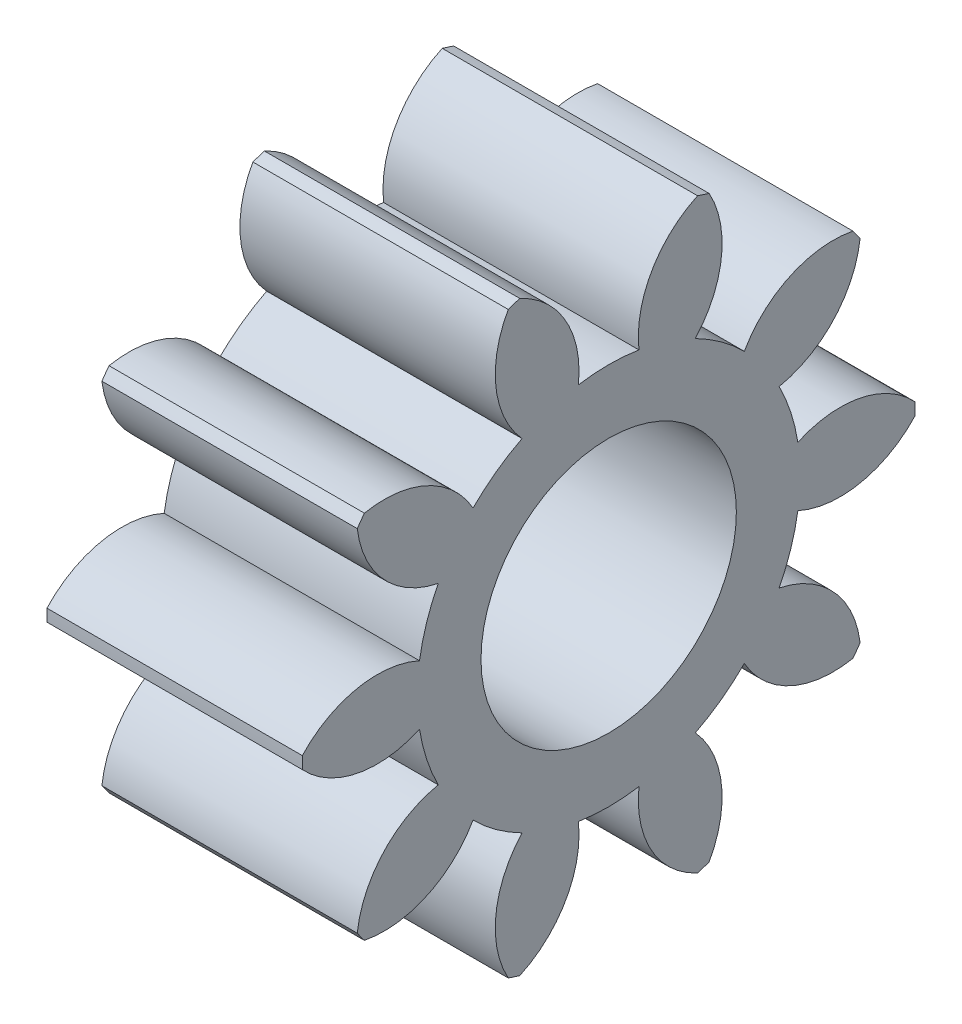
SolidWorks part; units mm, degrees
ref_plane "Plane1" through (0, 0, 0) normal (0, 0, 1) x (1, 0, 0)
ref_plane "Plane2" through (0, 0, 0) normal (0, 1, 0) x (1, 0, 0)
ref_plane "Plane3" through (0, 0, 0) normal (1, 0, 0) x (0, 0, -1)
sketch "HoldingSke" plane through (0, 0, 0) normal (0, 1, 0) x (1, 0, 0)
  line L0 (0, 0) -> (0.9848, -0.1736)
  line L1 (-15, 0) -> (100, 0) construction
  line L2 (0, 0) -> (-2.1039, 2.3779)
  line L3 (0, 0) -> (-11.863, 4.5341)
  line L4 (0, 0) -> (8.5048, 1.4996)
  line L5 (0, 0) -> (-46.8476, -17.4728)
  line L6 (0, 0) -> (-4.1448, -2.7965)
  line L7 (-2.1039, 2.3779) -> (8.6586, 51.2059)
  line L8 (-76.2, 54.61) -> (-75.3, 54.61)
  line L9 (-71.009, 38.7566) -> (-53.1078, 45.2721)
  line L10 (-76.2, 71.12) -> (104.1128, 71.12)
  line L11 (0, 0) -> (-5, 0)
  line L12 (-76.2, 101.6) -> (-76.162, 101.6)
  line L13 (24.9733, 27.94) -> (52.9518, 28.4284)
  line L14 (24.9733, 27.94) -> (24.9743, 27.94)
  line L15 (24.9733, 27.94) -> (100.4006, 29.5858)
  line L16 (-63.627, -1) -> (-12.827, -1)
  circle A0 centre (0, 0) radius 2.5
  circle A1 centre (0, 0) radius 3.749
  circle A2 centre (0, 0) radius 37.5
  circle A3 centre (0, 0) radius 2.5
  dimension "MHD" = 7.498
  dimension "Hub_dia" = 75
  dimension "Bore" = 5
  dimension "MBD" = 5
  dimension "Num_teeth" = 10
  dimension "Pitch" = 1
  dimension "Overall_len" = 50
  dimension "Show_teeth" = 10
  dimension "Thickness" = 5
  dimension "OAL" = 50.0001
  dimension "T_dim" = 0.9
  dimension "Ap" = 20
  dimension "H" = 19.05
  dimension "Pitch_radius" = 180.3128
  dimension "Width" = 5
  dimension "Backlash" = 0.038
  dimension "Addendum_fac" = 1
  dimension "Dedendum_fac" = 1.25
  dimension "Clearance_fac" = 0.25
  dimension "Dedendum_add" = 0.001
  dimension "Module" = 1
sketch "BasProSke" plane through (0, 0, 0) normal (0, 1, 0) x (1, 0, 0)
  line L0 (-10, 0) -> (60, 0) construction
  line L1 (0, 0) -> (0, 6)
  line L2 (0, 0) -> (5, 0)
  line L3 (5, 0) -> (5, 6)
  line L4 (5, 6) -> (0, 6)
  dimension "Thickness" = 5
  dimension "Diameter" = 12
revolve "Base-Revolve" add sketch "BasProSke" angle 360 about L0
sketch "TooCutSke" plane through (0, 0, 0) normal (1, 0, 0) x (0, 0, -1)
  line L1 (0, 0) -> (0, 107) construction
  line L2 (0, 0) -> (-0.8485, 4.9275) construction
  line L3 (0, 0) -> (-3.0584, 9.4126) construction
  line L4 (-0.8485, 4.9275) -> (-1.5292, 4.7063) construction
  arc A0 (0.5928, 3.7018) -> (-0.5928, 3.7018) centre (0, 0) ccw
  arc A1 (1.7758, 5.7578) -> (-1.7758, 5.7578) centre (0, 0) ccw
  circle A2 centre (0, 0) radius 5 construction
  circle A3 centre (0, 0) radius 4.6985 construction
  arc A4 (-0.5928, 3.7018) -> (-1.7758, 5.7578) centre (-2.5801, 3.9267) ccw
  arc A5 (1.7758, 5.7578) -> (0.5928, 3.7018) centre (2.5801, 3.9267) ccw
  dimension "Root_dia" = 7.498
  dimension "Overcut_dia" = 12.0508
  dimension "Pitch_dia" = 10
  dimension "Base_dia" = 9.3969
  dimension "Flank_rad" = 2
  dimension "Half_ang" = 18
  dimension "Half_CT" = 0.7157
extrude "ToothCut" cut sketch "TooCutSke" along normal through all
fillet "Breaks" [suppressed] radius 0.02
fillet "RootFillets" [suppressed] radius 0.251
pattern_circular "TeethCuts" count 10 every 36 about axis through (-10, 0, 0) along (1, 0, 0) of "ToothCut", "RootFillets", "Breaks"
sketch "HubNeaOneSke" plane through (0, 0, 0) normal (-1, 0, 0) x (0, 0, 1)
  circle A0 centre (0, 0) radius 3.749
  dimension "Diameter" = 7.498
extrude "HubNearOne" [suppressed] add sketch "HubNeaOneSke" along normal blind 45.0001
sketch "HubNeaBotSke" plane through (0, 0, 0) normal (-1, 0, 0) x (0, 0, 1)
  circle A0 centre (0, 0) radius 3.749
  dimension "Diameter" = 7.498
extrude "HubNearBoth" [suppressed] add sketch "HubNeaBotSke" along normal blind 22.5
ref_plane "FarPln" through (5, 0, 0) normal (1, 0, 0) x (0, 0, -1)
sketch "HubFarSke" plane through (5, 0, 0) normal (1, 0, 0) x (0, 0, -1)
  circle A0 centre (0, 0) radius 3.749
  dimension "Diameter" = 7.498
extrude "HubFar" [suppressed] add sketch "HubFarSke" along normal blind 22.5
sketch "BorSke" plane through (0, 0, 0) normal (1, 0, 0) x (0, 0, -1)
  circle A0 centre (0, 0) radius 2.5
  dimension "Diameter" = 5
extrude "Bore" cut sketch "BorSke" along normal mid plane 100.0001
sketch "KeySke" plane through (0, 0, 0) normal (1, 0, 0) x (0, 0, -1)
  line L0 (-1, 0) -> (-1, 3.4)
  line L1 (-1, 3.4) -> (1, 3.4)
  line L2 (1, 3.4) -> (1, 0)
  line L3 (0, 0) -> (0, 34) construction
  line L4 (-1, 0) -> (1, 0)
  dimension "Offset" = 3.4
  dimension "Width" = 2
extrude "Keyway" [suppressed] cut sketch "KeySke" along normal mid plane 100.0001
pattern_circular "Keyway2" [suppressed] count 2 every 90 about axis through (-10, 0, 0) along (1, 0, 0)
equation "' \"Module@HoldingSke\" = 6.35"
equation "' \"Num_teeth@HoldingSke\" = 12"
equation "' \"Ap@HoldingSke\" =  20"
equation "' \"Ap@HoldingSke\" = 20"
equation "' \"Width@HoldingSke\" = 0.5 * 25.4"
equation "' \"Hub_dia@HoldingSke\"= 1 * 25.4"
equation "' \"Hub_dia@HoldingSke\" = 1 * 25.4"
equation "' \"Overall_len@HoldingSke\" = 1.0 * 25.4"
equation "' \"Bore@HoldingSke\" = 0.75 * 25.4"
equation "' \"T_dim@HoldingSke\" = 0.1 * 25.4"
equation "' \"Width@KeySke\" = 0.25 * 25.4"
equation "' \"Show_teeth@HoldingSke\" = 13"
equation "' \"Backlash@HoldingSke\" = 0.009 * 25.4"
equation "' \"Addendum_fac@HoldingSke\" = 1.0"
equation "' \"Dedendum_fac@HoldingSke\" = 1.25"
equation "' \"Dedendum_add@HoldingSke\" = 0.00005 * 25.4"
equation "' \"Clearance_fac@HoldingSke\" = 0.25"
equation "\"Pitch@HoldingSke\" = 1 / \"Module@HoldingSke\""
equation "\"Overcut_dia@TooCutSke\" = (\"Num_teeth@HoldingSke\" + 2 * \"Addendum_fac@HoldingSke\") / \"Pitch@HoldingSke\" + 0.002 * 25.4"
equation "\"Pitch_dia@TooCutSke\" = \"Num_teeth@HoldingSke\" / \"Pitch@HoldingSke\""
equation "\"Base_dia@TooCutSke\" = \"Num_teeth@HoldingSke\" / \"Pitch@HoldingSke\" * cos((\"Ap@HoldingSke\"  * 3.14159265 / 180))"
equation "\"Root_dia@TooCutSke\" = (\"Num_teeth@HoldingSke\" + 2) / \"Pitch@HoldingSke\" - 2 * (\"Addendum_fac@HoldingSke\" + \"Dedendum_fac@HoldingSke\") / \"Pitch@HoldingSke\" - \"Dedendum_add@HoldingSke\" * 2"
equation "\"Half_ang@TooCutSke\" = 180 / \"Num_teeth@HoldingSke\""
equation "\"Half_CT@TooCutSke\" = \"Num_teeth@HoldingSke\" / \"Pitch@HoldingSke\" * sin((3.14159265 / 2 / \"Num_teeth@HoldingSke\")) / 2 - 7 * \"Backlash@HoldingSke\" / 4"
equation "\"Flank_rad@TooCutSke\" = \"Num_teeth@HoldingSke\" / \"Pitch@HoldingSke\" / 5"
equation "\"Radius@RootFillets\" = \"Clearance_fac@HoldingSke\" / \"Pitch@HoldingSke\" + \"Dedendum_add@HoldingSke\""
equation "\"Break_rad@Breaks\" = 0.02 / \"Pitch@HoldingSke\""
equation "\"Thickness@HoldingSke\" = \"Width@HoldingSke\""
equation "\"OAL@HoldingSke\" = \"Thickness@HoldingSke\""
equation "\"MHD@HoldingSke\" = (\"Num_teeth@HoldingSke\" + 2) / \"Pitch@HoldingSke\" - 2 * (\"Addendum_fac@HoldingSke\" + \"Dedendum_fac@HoldingSke\")  / \"Pitch@HoldingSke\" - \"Dedendum_add@HoldingSke\" * 2"
equation "\"MBD@HoldingSke\" = (\"Num_teeth@HoldingSke\" + 2) / \"Pitch@HoldingSke\" - 2 * (\"Addendum_fac@HoldingSke\" + \"Dedendum_fac@HoldingSke\")  / \"Pitch@HoldingSke\" - \"Dedendum_add@HoldingSke\" * 2 - 0.002 * 25.4"
equation "\"MHD@HoldingSke\" = ((sgn( \"MHD@HoldingSke\" - \"Hub_dia@HoldingSke\" )-1)*( \"MHD@HoldingSke\" - \"Hub_dia@HoldingSke\" ))/-2+ \"Hub_dia@HoldingSke\""
equation "\"MBD@HoldingSke\" = ((sgn( \"MBD@HoldingSke\" - \"Bore@HoldingSke\" )-1)*( \"MBD@HoldingSke\" - \"Bore@HoldingSke\" ))/-2+ \"Bore@HoldingSke\""
equation "\"OAL@HoldingSke\" = ((sgn( \"OAL@HoldingSke\" - \"Overall_len@HoldingSke\" )+1)*( \"OAL@HoldingSke\" - \"Overall_len@HoldingSke\" ))/2 + \"Overall_len@HoldingSke\" + 0.000002 * 25.4"
equation "\"Num_teeth@TeethCuts\" = int( \"Show_teeth@HoldingSke\" ) + 1"
equation "\"Num_teeth@TeethCuts\" = ((sgn( \"Num_teeth@TeethCuts\" - \"Num_teeth@HoldingSke\" )-1)*( \"Num_teeth@TeethCuts\" - \"Num_teeth@HoldingSke\" ))/-2+ \"Num_teeth@HoldingSke\""
equation "\"Num_teeth@TeethCuts\" = ((sgn( \"Num_teeth@TeethCuts\" - 2.0)+1)*( \"Num_teeth@TeethCuts\" - 2.0))/2 +2.0"
equation "\"Angle@TeethCuts\" = 360.0 / \"Num_teeth@HoldingSke\""
equation "\"Diameter@BasProSke\" = (\"Num_teeth@HoldingSke\" + 2 * \"Addendum_fac@HoldingSke\") / \"Pitch@HoldingSke\""
equation "\"Thickness@BasProSke\"  = \"Thickness@HoldingSke\""
equation "' \"Fillet_rad@BasProSke\" =  \"Thickness@HoldingSke\" * 0.05"
equation "' \"Fillet_rad@BasProSke\" = \"Thickness@HoldingSke\" * 0.05"
equation "\"MHD@HoldingSke\" = ((sgn( \"MHD@HoldingSke\" - \"Root_dia@TooCutSke\" )-1)*( \"MHD@HoldingSke\" - \"Root_dia@TooCutSke\" ))/-2+ \"Root_dia@TooCutSke\""
equation "\"Diameter@HubNeaOneSke\" = \"MHD@HoldingSke\""
equation "\"Length@HubNearOne\" = \"OAL@HoldingSke\" - \"Thickness@BasProSke\""
equation "\"Diameter@HubNeaBotSke\" = \"MHD@HoldingSke\""
equation "\"Length@HubNearBoth\" = ( \"OAL@HoldingSke\" - \"Thickness@BasProSke\" ) / 2.0"
equation "\"Thickness@FarPln\" = \"Thickness@BasProSke\""
equation "\"Diameter@HubFarSke\" = \"MHD@HoldingSke\""
equation "\"Length@HubFar\" = ( \"OAL@HoldingSke\" - \"Thickness@BasProSke\" ) / 2.0"
equation "\"Diameter@BorSke\" = \"MBD@HoldingSke\""
equation "\"D1@Bore\" = \"OAL@HoldingSke\" * 2.0"
equation "\"D1@Keyway\" = \"OAL@HoldingSke\" * 2.0"
equation "\"Offset@KeySke\" = \"T_dim@HoldingSke\" + \"MBD@HoldingSke\" / 2.0"
